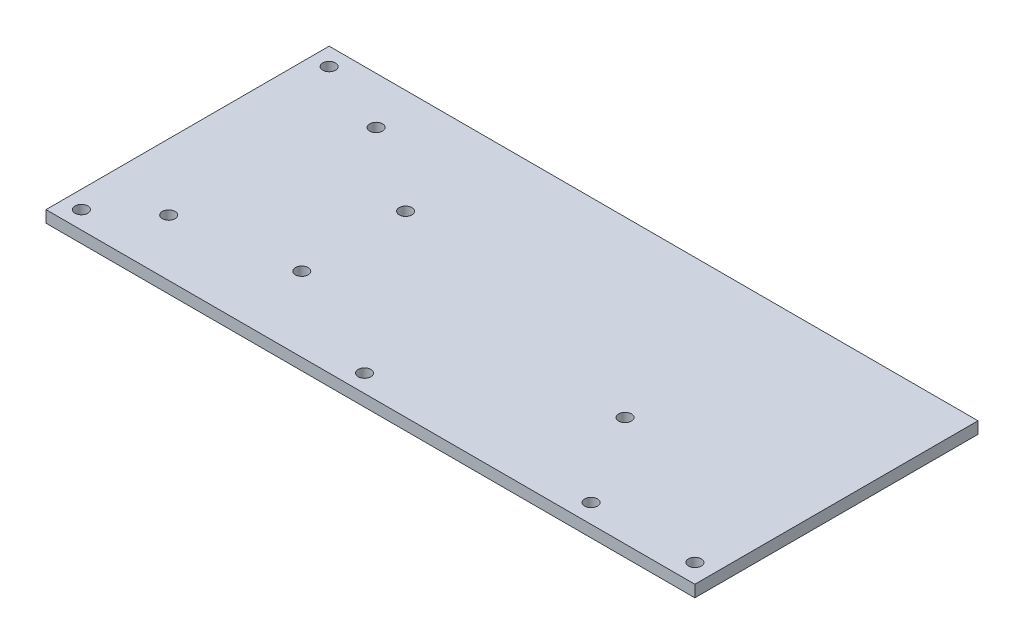
SolidWorks part; units mm, degrees
material "ABS"
ref_plane "Front Plane" through (0, 0, 0) normal (0, 0, 1) x (1, 0, 0)
ref_plane "Top Plane" through (0, 0, 0) normal (0, 1, 0) x (1, 0, 0)
ref_plane "Right Plane" through (0, 0, 0) normal (1, 0, 0) x (0, 0, -1)
sketch "Base Sketch" plane through (0, 0, 0) normal (0, 1, 0) x (1, 0, 0)
  line L1 (-87.3125, -38.1) -> (87.3125, -38.1)
  line L2 (-87.3125, -38.1) -> (-87.3125, 38.1)
  line L3 (-87.3125, 38.1) -> (87.3125, 38.1)
  line L4 (87.3125, -38.1) -> (87.3125, 38.1)
  line L5 (-87.3125, -38.1) -> (87.3125, 38.1) construction
  line L6 (-87.3125, 38.1) -> (87.3125, -38.1) construction
  point P0 (0, 0)
  dimension "D1" = 174.625
  dimension "D2" = 76.2
extrude "Base Plate" add sketch "Base Sketch" along normal blind 3.175
sketch "4-40 Hole Pattern Sketch (Guide Rail)" plane through (0, 3.175, 0) normal (0, 1, 0) x (1, 0, 0)
  line L0 (87.3125, 38.1) -> (-87.3125, 38.1) construction
  line L1 (-87.3125, 38.1) -> (-87.3125, -38.1) construction
  line L2 (-87.3125, -38.1) -> (87.3125, -38.1) construction
  circle A0 centre (-82.55, 33.3375) radius 1.7145
  circle A1 centre (-82.55, -33.3375) radius 1.7145
  circle A3 centre (-6.35, -33.3375) radius 1.7145
  point P0 (-82.55, 33.3375)
  point P6 (-82.55, -33.3375)
  dimension "D7" = 3.429
  dimension "D8" = 3.429
  dimension "D10" = 3.429
  dimension "D11" = 76.2
  dimension "D12" = 4.7625
  dimension "D1" = 4.7625
  dimension "D2" = 4.7625
  dimension "D5" = 4.7625
  dimension "D6" = 4.7625
sketch "4-40 Hole Pattern Sketch (Arduino Holes)" plane through (0, 3.175, 0) normal (0, 1, 0) x (1, 0, 0)
  line L2 (-87.3125, -38.1) -> (87.3125, -38.1) construction
  line L3 (-87.3125, 38.1) -> (-87.3125, -38.1) construction
  circle A0 centre (-38.5445, -18.034) radius 1.7145
  circle A1 centre (-38.5445, 9.906) radius 1.7145
  circle A6 centre (-69.5325, -22.86) radius 1.7145
  circle A7 centre (-62.0395, 25.4762) radius 1.7145
  dimension "D9" = 4.826
  dimension "D10" = 3.429
  dimension "D11" = 27.94
  dimension "D12" = 30.988
  dimension "D19" = 3.429
  dimension "D20" = 3.429
  dimension "D3" = 15.24
  dimension "D4" = 17.78
  dimension "D5" = 48.3362
  dimension "D6" = 7.493
  dimension "D7" = 3.429
  dimension "D8" = 30.988
extrude "4-40 Guide Rail Holes" cut sketch "4-40 Hole Pattern Sketch (Guide Rail)" against normal up to next
extrude "4-40 Arduino Holes" cut sketch "4-40 Hole Pattern Sketch (Arduino Holes)" against normal up to next
sketch "4-40 Hole Pattern Sketch (IMU Mount)" plane through (0, 3.175, 0) normal (0, 1, 0) x (1, 0, 0)
  line L0 (87.3125, -38.1) -> (87.3125, 38.1) construction
  line L1 (-87.3125, -38.1) -> (87.3125, -38.1) construction
  circle A0 centre (82.2325, -33.02) radius 1.7145
  circle A1 centre (54.2925, -33.02) radius 1.7145
  circle A2 centre (39.0525, -8.636) radius 1.7145
  dimension "D1" = 3.429
  dimension "D2" = 5.08
  dimension "D3" = 5.08
  dimension "D4" = 3.429
  dimension "D5" = 5.08
  dimension "D6" = 27.94
  dimension "D7" = 3.429
  dimension "D8" = 24.384
  dimension "D9" = 43.18
extrude "4-40 IMU Mount Holes" cut sketch "4-40 Hole Pattern Sketch (IMU Mount)" against normal up to next
